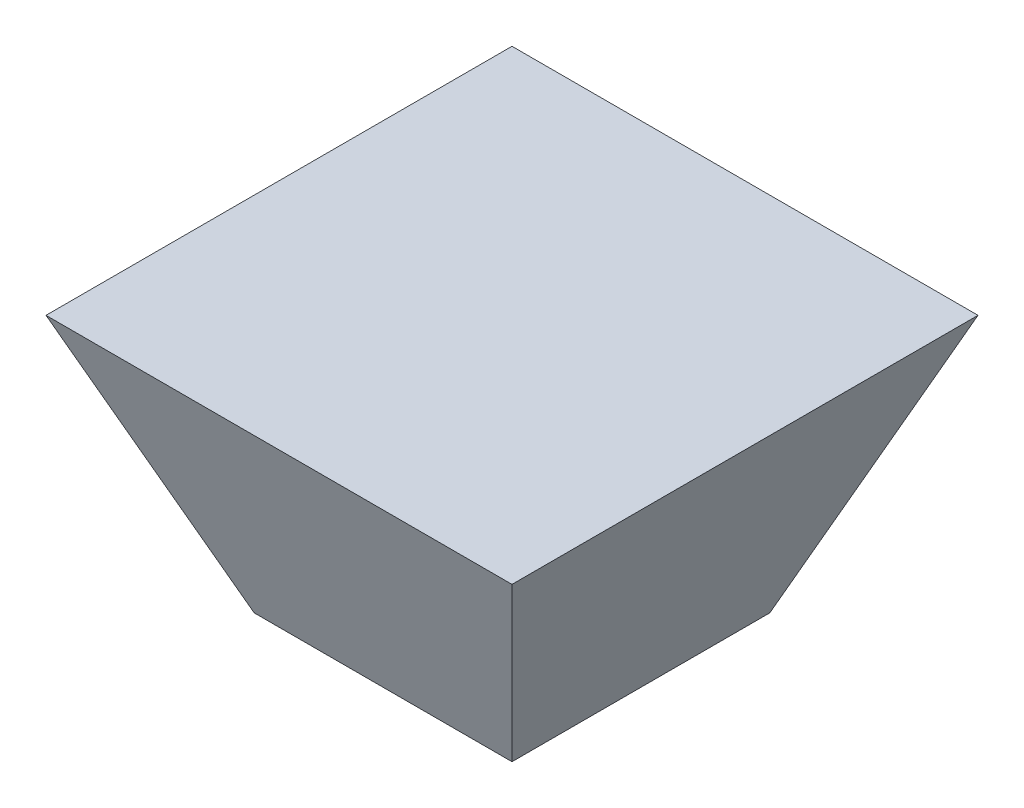
SolidWorks part; units mm, degrees
ref_plane "Front Plane" through (0, 0, 0) normal (0, 0, 1) x (1, 0, 0)
ref_plane "Top Plane" through (0, 0, 0) normal (0, 1, 0) x (1, 0, 0)
ref_plane "Right Plane" through (0, 0, 0) normal (1, 0, 0) x (0, 0, -1)
sketch "Sketch1" plane through (0, 0, 0) normal (0, 1, 0) x (1, 0, 0)
  line L1 (-56.35, 56.35) -> (56.35, 56.35)
  line L2 (-56.35, 56.35) -> (-56.35, -56.35)
  line L3 (-56.35, -56.35) -> (56.35, -56.35)
  line L4 (56.35, 56.35) -> (56.35, -56.35)
  line L5 (-56.35, 56.35) -> (56.35, -56.35) construction
  line L6 (-56.35, -56.35) -> (56.35, 56.35) construction
  point P0 (0, 0)
  dimension "D1" = 112.7
  dimension "D2" = 112.7
extrude "Boss-Extrude2" add sketch "Sketch1" along normal blind 112.7 draft 22 contours L1 L4 L3 L2 draft outward yes
